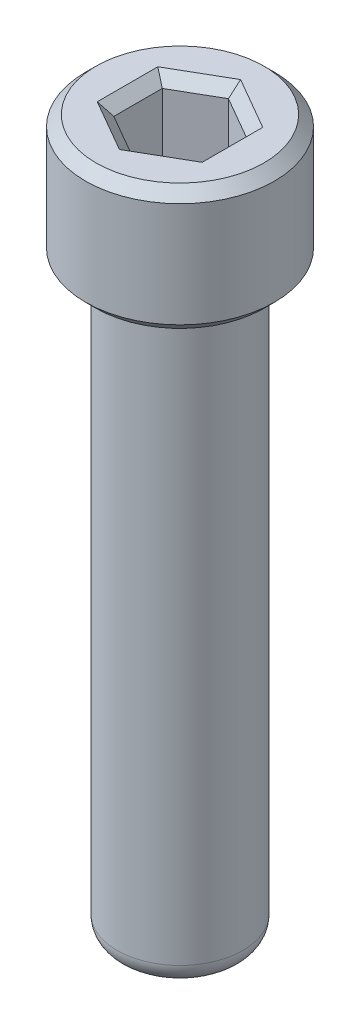
SolidWorks part; units mm, degrees
ref_plane "Front Plane" through (0, 0, 0) normal (0, 0, 1) x (1, 0, 0)
ref_plane "Top Plane" through (0, 0, 0) normal (0, 1, 0) x (1, 0, 0)
ref_plane "Right Plane" through (0, 0, 0) normal (1, 0, 0) x (0, 0, -1)
sketch "Sketch1" plane through (0, 0, 0) normal (0, 1, 0) x (1, 0, 0)
  circle A0 centre (0, 0) radius 1.5
  dimension "D1" = 3
extrude "Boss-Extrude1" add sketch "Sketch1" along normal blind 14
sketch "Sketch2" plane through (0, 14, 0) normal (0, 1, 0) x (1, 0, 0)
  circle A0 centre (0, 0) radius 2.25
  dimension "D1" = 4.5
extrude "Boss-Extrude2" add sketch "Sketch2" along normal blind 3
sketch "Sketch3" plane through (0, 17, 0) normal (0, 1, 0) x (1, 0, 0)
  line L1 (0, 1.1547) -> (-1, 0.5774)
  line L2 (-1, 0.5774) -> (-1, -0.5774)
  line L3 (-1, -0.5774) -> (0, -1.1547)
  line L4 (0, -1.1547) -> (1, -0.5774)
  line L5 (1, -0.5774) -> (1, 0.5774)
  line L6 (1, 0.5774) -> (0, 1.1547)
  circle A0 centre (0, 0) radius 1 construction
extrude "Cut-Extrude1" cut sketch "Sketch3" against normal blind 2
chamfer "Chamfer1" distance 0.25 angle 45 8 edges at (0, 14, 2.25) (0, 17, 2.25) (-0.5, 17, 0.866) (-1, 17, 0) (-0.5, 17, -0.866) (0.5, 17, -0.866) (1, 17, 0) (0.5, 17, 0.866)
fillet "Fillet1" radius 0.5 1 edges at (0, 0, 1.5)
